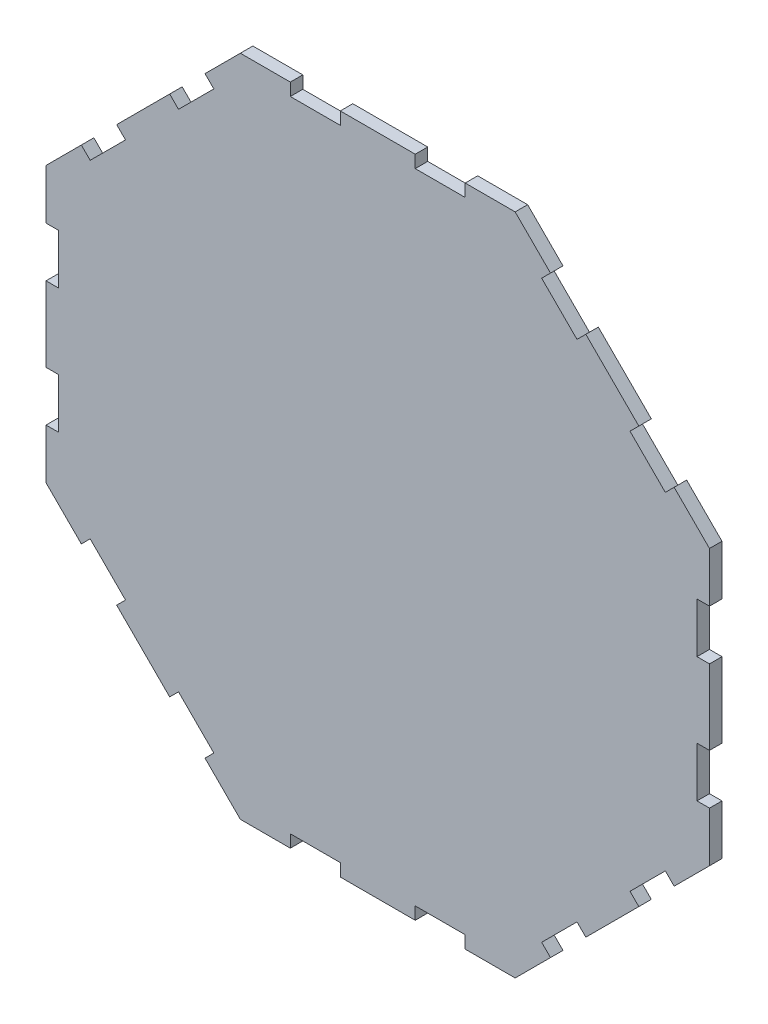
SolidWorks part; units mm, degrees
ref_plane "Front Plane" through (0, 0, 0) normal (0, 0, 1) x (1, 0, 0)
ref_plane "Top Plane" through (0, 0, 0) normal (0, 1, 0) x (1, 0, 0)
ref_plane "Right Plane" through (0, 0, 0) normal (1, 0, 0) x (0, 0, -1)
sketch "Sketch1" plane through (0, 0, 0) normal (0, 0, 1) x (1, 0, 0)
  line L0 (41.6602, 73.0911) -> (50.6404, 64.1108)
  line L1 (-84.3164, 34.925) -> (-84.3164, -34.925)
  line L2 (-84.3164, -34.925) -> (-34.925, -84.3164)
  line L3 (-34.925, -84.3164) -> (34.925, -84.3164)
  line L4 (34.925, -84.3164) -> (84.3164, -34.925)
  line L5 (84.3164, -34.925) -> (84.3164, 34.925)
  line L6 (84.3164, 34.925) -> (34.925, 84.3164)
  line L7 (34.925, 84.3164) -> (-34.925, 84.3164)
  line L8 (-34.925, 84.3164) -> (-84.3164, 34.925)
  line L9 (-22.225, 84.3164) -> (-9.525, 84.3164)
  line L10 (-22.225, 84.3164) -> (-22.225, 81.1414)
  line L11 (-22.225, 81.1414) -> (-9.525, 81.1414)
  line L12 (-9.525, 84.3164) -> (-9.525, 81.1414)
  line L13 (22.225, 84.3164) -> (9.525, 84.3164)
  line L14 (22.225, 84.3164) -> (22.225, 81.1414)
  line L15 (22.225, 81.1414) -> (9.525, 81.1414)
  line L16 (9.525, 84.3164) -> (9.525, 81.1414)
  line L17 (52.8855, 66.3559) -> (50.6404, 64.1108)
  line L18 (43.9053, 75.3362) -> (41.6602, 73.0911)
  line L19 (73.0911, 41.6602) -> (64.1108, 50.6404)
  line L20 (66.3559, 52.8855) -> (64.1108, 50.6404)
  line L21 (75.3362, 43.9053) -> (73.0911, 41.6602)
  line L22 (81.1414, 22.225) -> (81.1414, 9.525)
  line L23 (84.3164, 9.525) -> (81.1414, 9.525)
  line L24 (84.3164, 22.225) -> (81.1414, 22.225)
  line L25 (81.1414, -22.225) -> (81.1414, -9.525)
  line L26 (84.3164, -9.525) -> (81.1414, -9.525)
  line L27 (84.3164, -22.225) -> (81.1414, -22.225)
  line L28 (73.0911, -41.6602) -> (64.1108, -50.6404)
  line L29 (66.3559, -52.8855) -> (64.1108, -50.6404)
  line L30 (75.3362, -43.9053) -> (73.0911, -41.6602)
  line L31 (41.6602, -73.0911) -> (50.6404, -64.1108)
  line L32 (52.8855, -66.3559) -> (50.6404, -64.1108)
  line L33 (43.9053, -75.3362) -> (41.6602, -73.0911)
  line L34 (22.225, -81.1414) -> (9.525, -81.1414)
  line L35 (9.525, -84.3164) -> (9.525, -81.1414)
  line L36 (22.225, -84.3164) -> (22.225, -81.1414)
  line L37 (-22.225, -81.1414) -> (-9.525, -81.1414)
  line L38 (-9.525, -84.3164) -> (-9.525, -81.1414)
  line L39 (-22.225, -84.3164) -> (-22.225, -81.1414)
  line L40 (-41.6602, -73.0911) -> (-50.6404, -64.1108)
  line L41 (-52.8855, -66.3559) -> (-50.6404, -64.1108)
  line L42 (-43.9053, -75.3362) -> (-41.6602, -73.0911)
  line L43 (-73.0911, -41.6602) -> (-64.1108, -50.6404)
  line L44 (-66.3559, -52.8855) -> (-64.1108, -50.6404)
  line L45 (-75.3362, -43.9053) -> (-73.0911, -41.6602)
  line L46 (-81.1414, -22.225) -> (-81.1414, -9.525)
  line L47 (-84.3164, -9.525) -> (-81.1414, -9.525)
  line L48 (-84.3164, -22.225) -> (-81.1414, -22.225)
  line L49 (-81.1414, 22.225) -> (-81.1414, 9.525)
  line L50 (-84.3164, 9.525) -> (-81.1414, 9.525)
  line L51 (-84.3164, 22.225) -> (-81.1414, 22.225)
  line L52 (-73.0911, 41.6602) -> (-64.1108, 50.6404)
  line L53 (-66.3559, 52.8855) -> (-64.1108, 50.6404)
  line L54 (-75.3362, 43.9053) -> (-73.0911, 41.6602)
  line L55 (-41.6602, 73.0911) -> (-50.6404, 64.1108)
  line L56 (-52.8855, 66.3559) -> (-50.6404, 64.1108)
  line L57 (-43.9053, 75.3362) -> (-41.6602, 73.0911)
  circle A0 centre (0, 0) radius 84.3164 construction
  point P77 (0, 0)
  dimension "D1" = 3.175
  dimension "D2" = 3.175
  dimension "D3" = 8
  dimension "D4" = 12.7
  dimension "D5" = 12.7
  dimension "D6" = 12.7
  dimension "D7" = 12.7
extrude "Boss-Extrude1" add sketch "Sketch1" along normal blind 3.175
